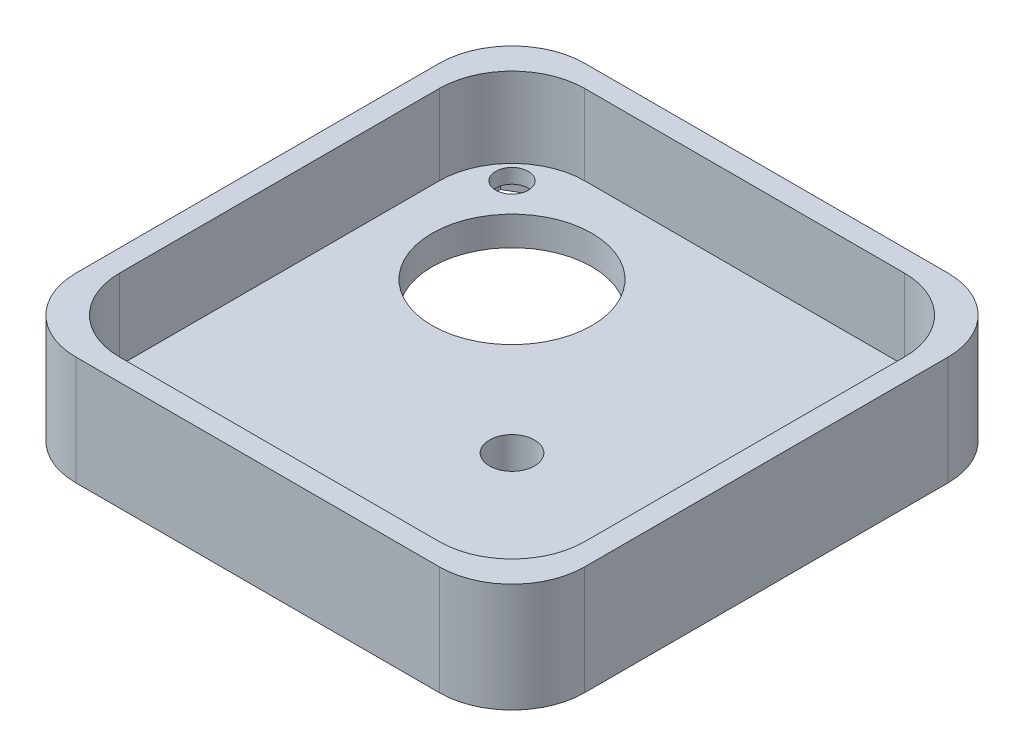
SolidWorks part; units mm, degrees
ref_plane "Front Plane" through (0, 0, 0) normal (0, 0, 1) x (1, 0, 0)
ref_plane "Top Plane" through (0, 0, 0) normal (0, 1, 0) x (1, 0, 0)
ref_plane "Right Plane" through (0, 0, 0) normal (1, 0, 0) x (0, 0, -1)
sketch "Sketch1" plane through (0, 0, 0) normal (0, 1, 0) x (1, 0, 0)
  line L0 (-50.25, 60) -> (-50.25, 70) construction
  line L1 (-10, 0) -> (-60, 0)
  line L2 (0, 10) -> (0, 60)
  line L3 (-10, 70) -> (-60, 70)
  line L4 (-70, 10) -> (-70, 60)
  line L5 (-60, 50.25) -> (-70, 50.25) construction
  line L6 (-50.25, 50.25) -> (-29.5671, 29.5671) construction
  line L7 (-29.5671, 10.0671) -> (-29.5671, 0) construction
  line L8 (-10.0671, 29.5671) -> (0, 29.5671) construction
  circle A0 centre (-29.5671, 29.5671) radius 19.5
  circle A1 centre (-50.25, 50.25) radius 9.75
  arc A2 (-60, 0) -> (-70, 10) centre (-60, 10) cw
  arc A3 (-10, 0) -> (0, 10) centre (-10, 10) ccw
  arc A4 (0, 60) -> (-10, 70) centre (-10, 60) ccw
  arc A5 (-60, 70) -> (-70, 60) centre (-60, 60) ccw
  circle A6 centre (-50.25, 50.25) radius 2.5
  circle A7 centre (-29.5671, 29.5671) radius 2.5
  point P16 (-70, 0)
  point P19 (0, 0)
  point P24 (-70, 70)
  dimension "D3" = 39
  dimension "D4" = 19.5
  dimension "D8" = 10
  dimension "D9" = 5
  dimension "D10" = 5
  dimension "D7" = 45
  dimension "D1" = 70
  dimension "D2" = 70
  dimension "D5" = 10
  dimension "D6" = 10
extrude "Boss-Extrude2" add sketch "Sketch1" along normal blind 4 contours L3 A5 L4 A2 L1 A3 L2 A4 A0 A1 | A0 A7 | A1 A6
sketch "Sketch2" plane through (0, 4, 0) normal (0, 1, 0) x (1, 0, 0)
  line L0 (-3, 13) -> (-3, 57)
  line L1 (-10, 0) -> (-60, 0)
  line L2 (0, 10) -> (0, 60)
  line L3 (-10, 70) -> (-60, 70)
  line L4 (-70, 10) -> (-70, 60)
  line L5 (-13, 67) -> (-57, 67)
  line L6 (-67, 13) -> (-67, 57)
  line L7 (-13, 3) -> (-57, 3)
  line L8 (0, 0) -> (-70, 0) construction
  line L9 (-70, 0) -> (-70, 70) construction
  line L10 (-3, 3) -> (-67, 3) construction
  line L11 (-67, 3) -> (-67, 67) construction
  line L12 (-3, 3) -> (-3, 67) construction
  line L13 (0, 0) -> (0, 70) construction
  line L14 (-3, 67) -> (-67, 67) construction
  line L15 (0, 70) -> (-70, 70) construction
  line L16 (-70, 10) -> (-70, 60) construction
  line L17 (0, 10) -> (0, 60) construction
  line L18 (-10, 70) -> (-60, 70) construction
  arc A0 (-60, 0) -> (-70, 10) centre (-60, 10) cw
  arc A1 (-57, 3) -> (-67, 13) centre (-57, 13) cw
  arc A2 (-13, 3) -> (-3, 13) centre (-13, 13) ccw
  arc A3 (-10, 0) -> (0, 10) centre (-10, 10) ccw
  arc A4 (-3, 57) -> (-13, 67) centre (-13, 57) ccw
  arc A5 (0, 60) -> (-10, 70) centre (-10, 60) ccw
  arc A6 (-67, 57) -> (-57, 67) centre (-57, 57) cw
  arc A7 (-70, 60) -> (-60, 70) centre (-60, 60) cw
  dimension "D2" = 10
  dimension "D1" = 3
extrude "Boss-Extrude3" add sketch "Sketch2" along normal blind 11
sketch "Sketch4" plane through (0, 4, 0) normal (0, 1, 0) x (1, 0, 0)
  circle A0 centre (-50.25, 50.25) radius 11
  dimension "D1" = 22
extrude "Cut-Extrude1" cut sketch "Sketch4" against normal blind 6
sketch "Sketch5" plane through (0, 0, 0) normal (0, -1, 0) x (1, 0, 0)
  line L0 (-29.5671, -29.5671) -> (-29.5671, -39.5671) construction
  circle A0 centre (-29.5671, -29.5671) radius 10
  dimension "D1" = 20
extrude "Boss-Extrude5" add sketch "Sketch5" along normal blind 10
sketch "Sketch6" plane through (0, -10, 0) normal (0, -1, 0) x (1, 0, 0)
  line L0 (-29.5671, -29.5671) -> (-29.5671, -39.5671) construction
  line L2 (-32.4671, -34.6671) -> (-26.6671, -34.6671)
  line L3 (-32.4671, -34.6671) -> (-32.4671, -37.4671)
  line L4 (-32.4671, -37.4671) -> (-26.6671, -37.4671)
  line L5 (-26.6671, -34.6671) -> (-26.6671, -37.4671)
  circle A0 centre (-29.5671, -29.5671) radius 10 construction
  dimension "D1" = 2.8
  dimension "D2" = 5.8
  dimension "D3" = 2.9
  dimension "D4" = 2.1
extrude "Cut-Extrude2" cut sketch "Sketch6" against normal blind 8.8
sketch "Sketch7" plane through (0, -10, 0) normal (0, -1, 0) x (1, 0, 0)
  line L0 (-29.5671, -29.5671) -> (-29.5671, -39.5671) construction
  circle A0 centre (-29.5671, -29.5671) radius 10 construction
ref_plane "Plane1" through (-29.5671, -10, -39.5671) normal (0, 0, -1) x (-1, 0, 0)
sketch "Sketch8" plane through (-29.5671, -10, -39.5671) normal (0, 0, -1) x (-1, 0, 0)
  line L0 (0, 0) -> (0, 10) construction
  line L1 (-10, 0) -> (10, 0) construction
  line L2 (-10, 10) -> (10, 10) construction
  circle A0 centre (0, 5) radius 1.6
  dimension "D1" = 3.2
extrude "Cut-Extrude3" cut sketch "Sketch8" against normal blind 10
sketch "Sketch10" plane through (0, -10, 0) normal (0, -1, 0) x (1, 0, 0)
  circle A0 centre (-29.5671, -29.5671) radius 3.1
  dimension "D1" = 6.2
extrude "Cut-Extrude5" cut sketch "Sketch10" against normal through all
sketch "Sketch11" plane through (0, 4, 0) normal (0, 1, 0) x (1, 0, 0)
  line L0 (0, 10) -> (0, 60) construction
  line L1 (-10, 70) -> (-60, 70) construction
  line L2 (-35, 70) -> (-35, 0) construction
  line L3 (-60, 0) -> (-10, 0) construction
  line L4 (-70, 35) -> (0, 35) construction
  line L5 (-70, 60) -> (-70, 10) construction
  circle A0 centre (-8, 62) radius 2.25
  circle A1 centre (-62, 62) radius 2.25
  circle A2 centre (-62, 8) radius 2.25
  circle A3 centre (-8, 8) radius 2.25
  dimension "D1" = 4.5
  dimension "D2" = 8
  dimension "D3" = 8
extrude "Cut-Extrude6" cut sketch "Sketch11" against normal blind 10
sketch "Sketch12" plane through (0, 0, 0) normal (0, -1, 0) x (1, 0, 0)
  line L1 (-62, -3.6699) -> (-65.75, -5.8349)
  line L2 (-65.75, -5.8349) -> (-65.75, -10.1651)
  line L3 (-65.75, -10.1651) -> (-62, -12.3301)
  line L4 (-62, -12.3301) -> (-58.25, -10.1651)
  line L5 (-58.25, -10.1651) -> (-58.25, -5.8349)
  line L6 (-58.25, -5.8349) -> (-62, -3.6699)
  line L7 (-8, -3.6699) -> (-11.75, -5.8349)
  line L8 (-11.75, -5.8349) -> (-11.75, -10.1651)
  line L9 (-11.75, -10.1651) -> (-8, -12.3301)
  line L10 (-8, -12.3301) -> (-4.25, -10.1651)
  line L11 (-4.25, -10.1651) -> (-4.25, -5.8349)
  line L12 (-4.25, -5.8349) -> (-8, -3.6699)
  line L13 (-62, -57.6699) -> (-65.75, -59.8349)
  line L14 (-65.75, -59.8349) -> (-65.75, -64.1651)
  line L15 (-65.75, -64.1651) -> (-62, -66.3301)
  line L16 (-62, -66.3301) -> (-58.25, -64.1651)
  line L17 (-58.25, -64.1651) -> (-58.25, -59.8349)
  line L18 (-58.25, -59.8349) -> (-62, -57.6699)
  line L19 (-8, -57.6699) -> (-11.75, -59.8349)
  line L20 (-11.75, -59.8349) -> (-11.75, -64.1651)
  line L21 (-11.75, -64.1651) -> (-8, -66.3301)
  line L22 (-8, -66.3301) -> (-4.25, -64.1651)
  line L23 (-4.25, -64.1651) -> (-4.25, -59.8349)
  line L24 (-4.25, -59.8349) -> (-8, -57.6699)
  circle A0 centre (-62, -8) radius 3.75 construction
  circle A1 centre (-8, -8) radius 3.75 construction
  circle A2 centre (-62, -62) radius 3.75 construction
  circle A3 centre (-8, -62) radius 3.75 construction
  dimension "D1" = 7.5
  dimension "D2" = 7.5
  dimension "D3" = 7.5
  dimension "D4" = 7.5
extrude "Cut-Extrude7" cut sketch "Sketch12" against normal blind 2
